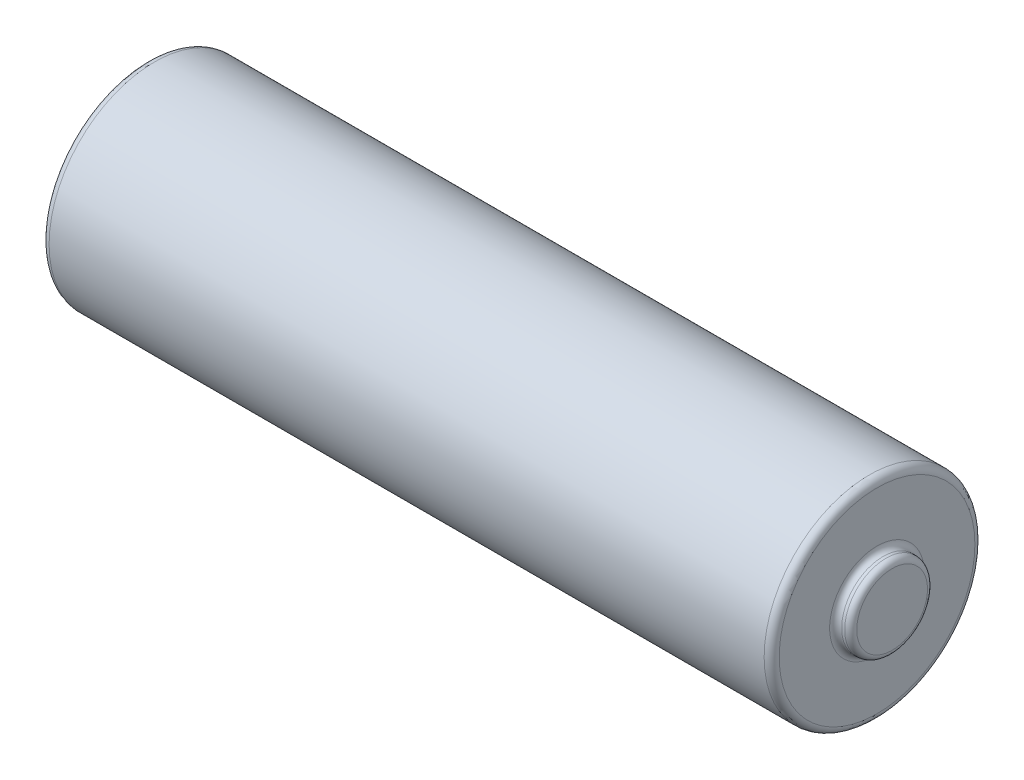
SolidWorks part; units mm, degrees
other "Heat zone"
other "line"
other "line1"
other "line2"
other "Test well"
other "TopLam"
other "Body"
other "PCB"
ref_plane "Front Plane" through (0, 0, 0) normal (0, 0, 1) x (1, 0, 0)
ref_plane "Top Plane" through (0, 0, 0) normal (0, 1, 0) x (1, 0, 0)
ref_plane "Right Plane" through (0, 0, 0) normal (1, 0, 0) x (0, 0, -1)
sketch "Sketch1" plane through (0, 0, 0) normal (0, 1, 0) x (1, 0, 0)
  line L0 (0, 0) -> (120, 0) construction
  line L1 (0, 0) -> (0, -14.5)
  line L2 (0, -14.5) -> (120, -14.5)
  line L3 (120, -14.5) -> (120, 14.5)
  line L4 (120, 14.5) -> (0, 14.5)
  line L5 (0, 14.5) -> (0, 0)
  dimension "D1" = 120
  dimension "D2" = 14.5
  dimension "D3" = 29
extrude "Boss-Extrude1" add sketch "Sketch1" along normal blind 2.75
sketch "Sketch2" plane through (0, 2.75, 0) normal (0, 1, 0) x (1, 0, 0)
  line L4 (0, 14.5) -> (0, -14.5)
  line L5 (0, -14.5) -> (120, -14.5)
  line L6 (120, -14.5) -> (120, 14.5)
  line L7 (120, 14.5) -> (0, 14.5)
  line L8 (0, 14.5) -> (0, -14.5)
  line L9 (0, -14.5) -> (120, -14.5)
  line L10 (120, -14.5) -> (120, 14.5)
  line L11 (120, 14.5) -> (0, 14.5)
  dimension "D1" = 0
extrude "Cut-Extrude1" cut sketch "Sketch2" against normal blind 0.125
sketch "Sketch3" plane through (0, 2.625, 0) normal (0, 1, 0) x (1, 0, 0)
  line L4 (120, 14.5) -> (0, 14.5)
  line L5 (0, 14.5) -> (0, -14.5)
  line L6 (0, -14.5) -> (120, -14.5)
  line L7 (120, -14.5) -> (120, 14.5)
  line L8 (120, 14.5) -> (0, 14.5)
  line L9 (0, 14.5) -> (0, -14.5)
  line L10 (0, -14.5) -> (120, -14.5)
  line L11 (120, -14.5) -> (120, 14.5)
  dimension "D1" = 0
extrude "Boss-Extrude2" add sketch "Sketch3" along normal blind 0.125 separate body
sketch "Sketch4" plane through (0, 2.625, 0) normal (0, 1, 0) x (1, 0, 0)
  line L0 (0, 0) -> (77.5, 0) construction
  line L1 (77.5, 0) -> (92.5, 0) construction
  line L2 (77.5, 0) -> (77.5, -2.5)
  line L3 (77.5, -2.5) -> (92.5, -2.5)
  line L4 (92.5, -2.5) -> (92.5, 2.5)
  line L5 (92.5, 2.5) -> (77.5, 2.5)
  line L6 (77.5, 2.5) -> (77.5, 0)
  dimension "D1" = 77.5
  dimension "D2" = 15
  dimension "D3" = 2.5
  dimension "D4" = 5
extrude "Cut-Extrude2" cut sketch "Sketch4" against normal blind 1.356
fillet "Fillet1" radius 2 4 edges at (77.5, 1.947, -2.5) (77.5, 1.947, 2.5) (92.5, 1.947, 2.5) (92.5, 1.947, -2.5)
sketch "Sketch5" plane through (0, 1.269, 0) normal (0, 1, 0) x (1, 0, 0)
  line L4 (90.5, 2.5) -> (79.5, 2.5)
  line L5 (77.5, 0.5) -> (77.5, -0.5)
  line L6 (79.5, -2.5) -> (90.5, -2.5)
  line L7 (92.5, -0.5) -> (92.5, 0.5)
  line L8 (90.5, 2.5) -> (79.5, 2.5)
  line L9 (77.5, 0.5) -> (77.5, -0.5)
  line L10 (79.5, -2.5) -> (90.5, -2.5)
  line L11 (92.5, -0.5) -> (92.5, 0.5)
  arc A4 (79.5, 2.5) -> (77.5, 0.5) centre (79.5, 0.5) ccw
  arc A5 (77.5, -0.5) -> (79.5, -2.5) centre (79.5, -0.5) ccw
  arc A6 (90.5, -2.5) -> (92.5, -0.5) centre (90.5, -0.5) ccw
  arc A7 (92.5, 0.5) -> (90.5, 2.5) centre (90.5, 0.5) ccw
  arc A8 (79.5, 2.5) -> (77.5, 0.5) centre (79.5, 0.5) ccw
  arc A9 (77.5, -0.5) -> (79.5, -2.5) centre (79.5, -0.5) ccw
  arc A10 (90.5, -2.5) -> (92.5, -0.5) centre (90.5, -0.5) ccw
  arc A11 (92.5, 0.5) -> (90.5, 2.5) centre (90.5, 0.5) ccw
  dimension "D1" = 0
extrude "Boss-Extrude3" add sketch "Sketch5" along normal blind 0.1 separate body
sketch "Sketch6" plane through (0, 1.369, 0) normal (0, 1, 0) x (1, 0, 0)
  line L0 (0, 0) -> (80, 0) construction
  line L1 (80, 0) -> (85, 0) construction
  line L2 (85, 0) -> (90, 0) construction
  line L3 (90, 2.5) -> (90, -2.5) construction
  line L4 (79.5, -2.5) -> (90.5, -2.5) construction
  line L5 (85, 2.5) -> (85, -2.5) construction
  line L6 (80, 2.5) -> (80, -2.5) construction
  line L7 (89.75, 2.5) -> (89.75, -2.5)
  line L8 (84.75, 2.5) -> (84.75, -2.5)
  line L9 (79.75, 2.5) -> (79.75, -2.5)
  line L10 (90.25, 2.5) -> (90.25, -2.5)
  line L11 (85.25, 2.5) -> (85.25, -2.5)
  line L12 (80.25, 2.5) -> (80.25, -2.5)
  line L13 (79.75, 2.5) -> (80.25, 2.5)
  line L14 (84.75, 2.5) -> (85.25, 2.5)
  line L15 (89.75, 2.5) -> (90.25, 2.5)
  line L16 (79.75, -2.5) -> (80.25, -2.5)
  line L17 (84.75, -2.5) -> (85.25, -2.5)
  line L18 (89.75, -2.5) -> (90.25, -2.5)
  point P10 (90, 0)
  point P13 (85, 0)
  point P16 (80, 0)
  dimension "D1" = 80
  dimension "D2" = 5
  dimension "D3" = 5
  dimension "D4" = 0.25
  dimension "D5" = 0.25
extrude "Boss-Extrude4" add sketch "Sketch6" along normal blind 0.1 separate body
sketch "Sketch7" plane through (0, 2.625, 0) normal (0, 1, 0) x (1, 0, 0)
  line L0 (0, 0) -> (29, 0) construction
  line L1 (29, 0) -> (59, 0) construction
  line L2 (59, 5) -> (59, -5)
  line L3 (59, -5) -> (29, -5)
  line L4 (29, -5) -> (29, 5)
  line L5 (29, 5) -> (59, 5)
  point P7 (59, 0)
  dimension "D1" = 29
  dimension "D2" = 30
  dimension "D3" = 10
extrude "Boss-Extrude5" add sketch "Sketch7" along normal blind 0.1 separate body
sketch "Sketch8" plane through (0, 2.625, 0) normal (0, 1, 0) x (1, 0, 0)
  line L0 (0, 0) -> (16.87, 0) construction
  ellipse E0 centre (16.87, 0) end of major axis (16.87, -5) minor radius 4
  dimension "D1" = 16.87
extrude "Cut-Extrude3" cut sketch "Sketch8" against normal blind 1.15
sketch "Sketch9" plane through (0, 2.75, 0) normal (0, 1, 0) x (1, 0, 0)
  line L0 (0, 0) -> (37, 0) construction
  line L1 (37, 14.5) -> (37, -14.5) construction
  line L2 (0, -14.5) -> (120, -14.5) construction
  line L3 (0, 0) -> (35, 0) construction
  line L4 (35, 14.5) -> (35, -14.5) construction
  line L5 (35.1, 2.5) -> (35.1, 4.5)
  line L6 (34.9, -1) -> (35.1, -1)
  line L7 (34.9, -1) -> (34.9, 1)
  line L8 (34.9, 1) -> (35.1, 1)
  line L9 (35.1, -1) -> (35.1, 1)
  line L10 (34.9, -1) -> (35.1, 1) construction
  line L11 (34.9, 1) -> (35.1, -1) construction
  line L12 (34.9, 2.5) -> (35.1, 2.5)
  line L13 (35.1, 6) -> (35.1, 8)
  line L14 (34.9, 6) -> (35.1, 6)
  line L15 (35.1, 9.5) -> (35.1, 11.5)
  line L16 (34.9, 9.5) -> (35.1, 9.5)
  line L17 (35.1, 13) -> (35.1, 15)
  line L18 (34.9, 13) -> (35.1, 13)
  line L19 (34.9, 2.5) -> (34.9, 4.5)
  line L20 (34.9, 4.5) -> (35.1, 4.5)
  line L21 (34.9, 6) -> (34.9, 8)
  line L22 (34.9, 8) -> (35.1, 8)
  line L23 (34.9, 13) -> (34.9, 15)
  line L24 (34.9, 15) -> (35.1, 15)
  line L25 (34.9, 9.5) -> (34.9, 11.5)
  line L26 (34.9, 11.5) -> (35.1, 11.5)
  line L27 (34.9, -11.5) -> (35.1, -11.5)
  line L28 (34.9, -9.5) -> (34.9, -11.5)
  line L29 (34.9, -15) -> (35.1, -15)
  line L30 (34.9, -13) -> (34.9, -15)
  line L31 (34.9, -8) -> (35.1, -8)
  line L32 (34.9, -6) -> (34.9, -8)
  line L33 (34.9, -4.5) -> (35.1, -4.5)
  line L34 (34.9, -2.5) -> (34.9, -4.5)
  line L35 (34.9, -13) -> (35.1, -13)
  line L36 (35.1, -13) -> (35.1, -15)
  line L37 (34.9, -9.5) -> (35.1, -9.5)
  line L38 (35.1, -9.5) -> (35.1, -11.5)
  line L39 (34.9, -6) -> (35.1, -6)
  line L40 (35.1, -6) -> (35.1, -8)
  line L41 (34.9, -2.5) -> (35.1, -2.5)
  line L42 (35.1, -2.5) -> (35.1, -4.5)
  point P8 (37, 0)
  point P12 (35, 0)
  dimension "D1" = 37
  dimension "D2" = 35
  dimension "D3" = 2
  dimension "D4" = 0.2
  dimension "D5" = 5
extrude "Cut-Extrude4" cut sketch "Sketch9" against normal through all both and the other way through all
sketch "Sketch10" plane through (0, 0, 0) normal (0, -1, 0) x (1, 0, 0)
  line L4 (0, 14.5) -> (0, -14.5)
  line L5 (0, -14.5) -> (120, -14.5)
  line L6 (120, -14.5) -> (120, 14.5)
  line L7 (120, 14.5) -> (0, 14.5)
  line L8 (0, 14.5) -> (0, -14.5)
  line L9 (0, -14.5) -> (120, -14.5)
  line L10 (120, -14.5) -> (120, 14.5)
  line L11 (120, 14.5) -> (0, 14.5)
  dimension "D1" = 0
extrude "Boss-Extrude6" add sketch "Sketch10" along normal blind 1.619 separate body
sketch "Sketch11" plane through (0, 0, 0) normal (1, 0, 0) x (0, 0, -1)
  line L0 (0, 0) -> (0, -1.619) construction
  line L1 (14.5, -1.619) -> (-14.5, -1.619) construction
  line L2 (0, -1.619) -> (0, -9.869) construction
  line L3 (0, -9.869) -> (8.1, -9.869) construction
  line L4 (0, -9.869) -> (-8.1, -9.869) construction
  circle A0 centre (8.1, -9.869) radius 7
  dimension "D4" = 14
  dimension "D1" = 8.25
  dimension "D2" = 8.1
  dimension "D3" = 8.1
extrude "Boss-Extrude7" add sketch "Sketch11" along normal blind 48.5 from offset 45 separate body
sketch "Sketch12" plane through (93.5, 0, 0) normal (1, 0, 0) x (0, 0, -1)
  circle A0 centre (8.1, -9.869) radius 4.25
  dimension "D1" = 8.5
extrude "Boss-Extrude8" add sketch "Sketch12" along normal blind 1
sketch "Sketch13" plane through (45, 0, 0) normal (-1, 0, 0) x (0, 0, 1)
  circle A0 centre (-8.1, -9.869) radius 2.75
  dimension "D1" = 5.5
extrude "Boss-Extrude9" add sketch "Sketch13" along normal blind 1
sketch "Sketch14" plane through (0, 0, 0) normal (1, 0, 0) x (0, 0, -1)
  circle A0 centre (-8.1, -9.869) radius 7
  dimension "D1" = 14
extrude "Boss-Extrude10" add sketch "Sketch14" along normal blind 48.5 from offset 44 separate body
ref_plane "Battery top plane" through (0, -9.869, 0) normal (0, 1, 0) x (1, 0, 0)
ref_plane "Battery front plane" through (0, 0, 8.1) normal (0, 0, 1) x (1, 0, 0)
sketch "Sketch15" plane through (92.5, 0, 0) normal (1, 0, 0) x (0, 0, -1)
  circle A0 centre (-8.1, -9.869) radius 2.75
  dimension "D1" = 5.5
extrude "Boss-Extrude11" add sketch "Sketch15" along normal blind 1
sketch "Sketch16" plane through (44, 0, 0) normal (-1, 0, 0) x (0, 0, 1)
  circle A0 centre (8.1, -9.869) radius 4.25
  dimension "D1" = 8.5
extrude "Boss-Extrude12" add sketch "Sketch16" along normal blind 1
fillet "Fillet2" radius 0.5 2 edges at (92.5, -9.869, 1.1) (44, -9.869, 1.1)
fillet "Fillet3" radius 0.5 2 edges at (93.5, -9.869, -15.1) (45, -9.869, -15.1)
fillet "Fillet4" radius 0.4 2 edges at (92.5, -9.869, 5.35) (93.5, -9.869, 5.35)
fillet "Fillet5" radius 0.4 2 edges at (93.5, -9.869, -12.35) (94.5, -9.869, -12.35)
fillet "Fillet6" radius 0.4 2 edges at (45, -9.869, -5.35) (44, -9.869, -5.35)
fillet "Fillet7" radius 0.4 2 edges at (44, -9.869, 12.35) (43, -9.869, 12.35)
delete or keep bodies "Body-Delete/Keep 1" type delete bodies bodies 106 107 108 109 110 111 112 115 105
